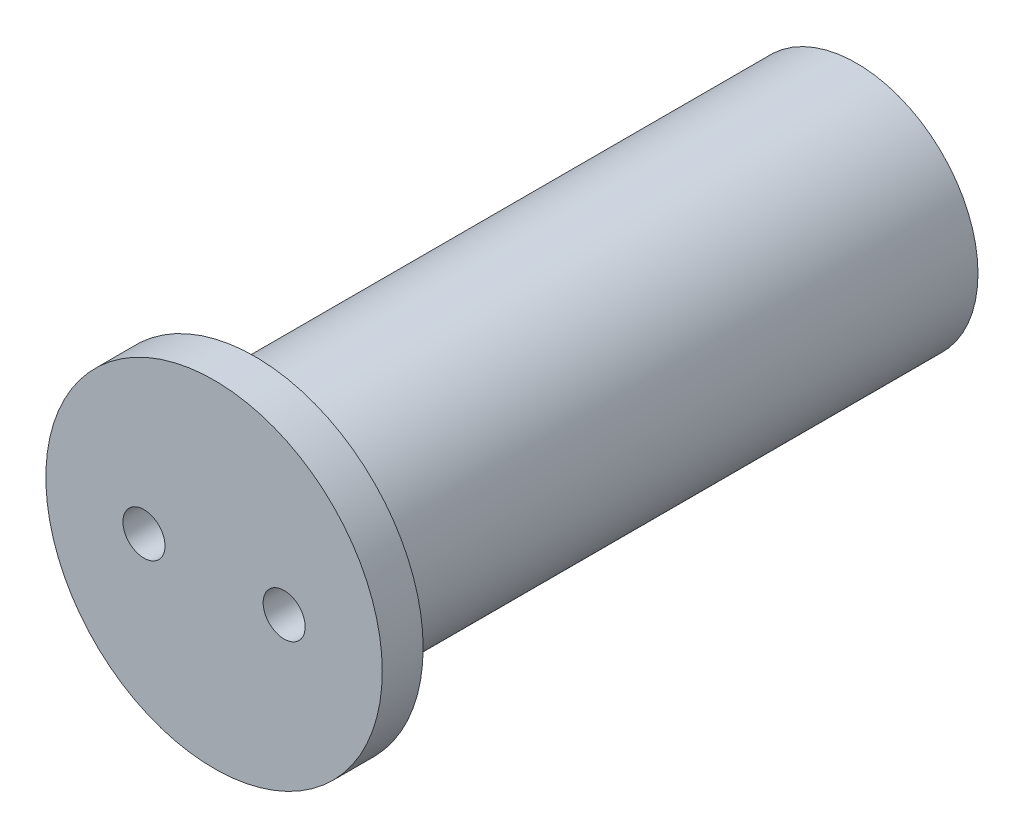
SolidWorks part; units mm, degrees
ref_plane "前视基准面" through (0, 0, 0) normal (0, 0, 1) x (1, 0, 0)
ref_plane "上视基准面" through (0, 0, 0) normal (0, 1, 0) x (1, 0, 0)
ref_plane "右视基准面" through (0, 0, 0) normal (1, 0, 0) x (0, 0, -1)
sketch "草图1" plane through (0, 0, 0) normal (0, 0, 1) x (1, 0, 0)
  circle A0 centre (0, 0) radius 5.2
extrude "凸台-拉伸1" add sketch "草图1" along normal blind 27.5
ref_plane "基准面4" through (0, 0, 13.75) normal (0, 0, 1) x (1, 0, 0)
sketch "草图3" plane through (0, 0, 27.5) normal (0, 0, 1) x (1, 0, 0)
  line L0 (0, 0) -> (0, 5.6384) construction
  circle A0 centre (-3, 0) radius 0.85
  circle A1 centre (3, 0) radius 0.85
  point P9 (0, 0)
  dimension "D1" = 1.7
  dimension "D2" = 3
  dimension "D3" = 2
sketch "草图6" plane through (0, 0, 27.5) normal (0, 0, 1) x (1, 0, 0)
  circle A0 centre (0, 0) radius 7.2
extrude "凸台-拉伸3" add sketch "草图6" against normal blind 1.75
extrude "切除-拉伸4" cut sketch "草图3" against normal blind 8
mirror "镜向3" about plane through (0, 0, 13.75) normal (0, 0, 1) of "切除-拉伸4"
sketch "草图7" plane through (0, 0, 27.5) normal (0, 0, 1) x (1, 0, 0)
  circle A0 centre (-3, 0) radius 0.9
  circle A1 centre (3, 0) radius 0.9
extrude "切除-拉伸5" cut sketch "草图7" against normal up to surface (8 mm away) up to face at (-2.15, 0, 19.5)
